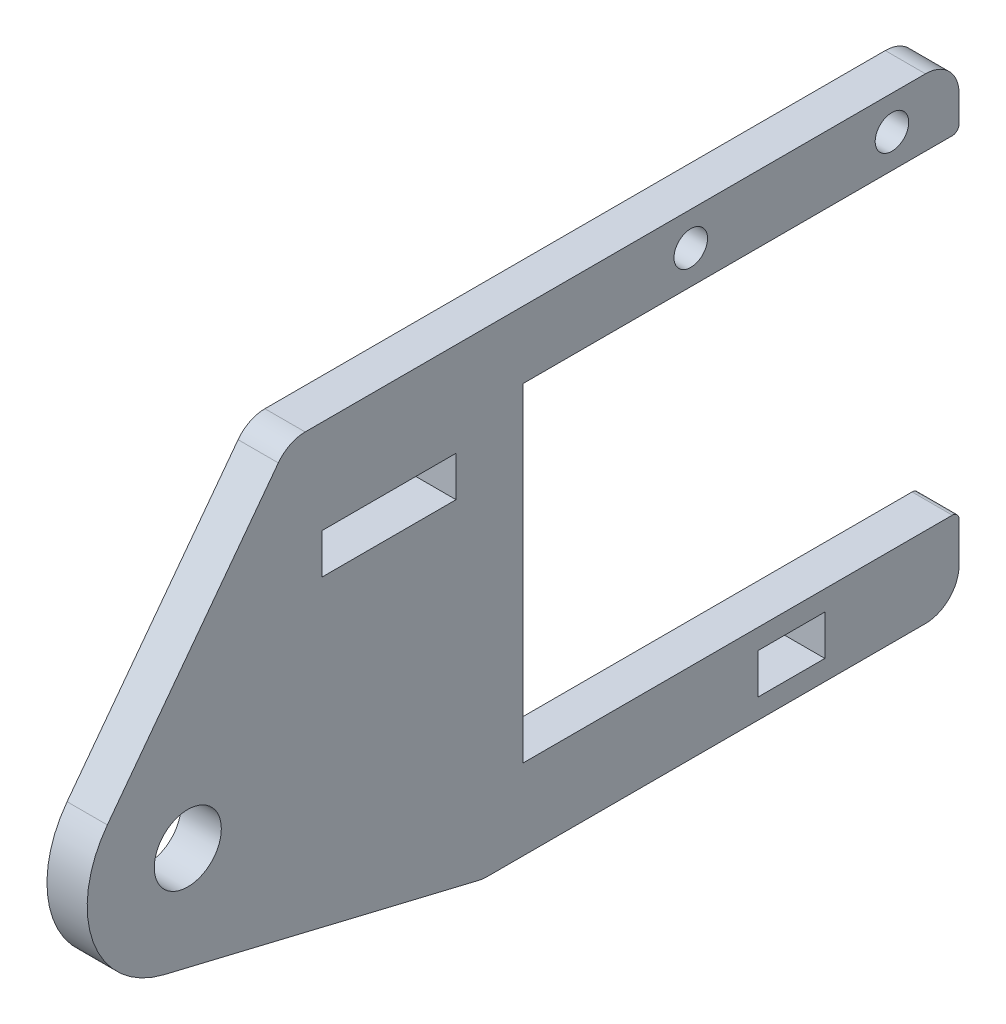
SolidWorks part; units mm, degrees
ref_plane "Front Plane" through (0, 0, 0) normal (0, 0, 1) x (1, 0, 0)
ref_plane "Top Plane" through (0, 0, 0) normal (0, 1, 0) x (1, 0, 0)
ref_plane "Right Plane" through (0, 0, 0) normal (1, 0, 0) x (0, 0, -1)
sketch "Sketch1" plane through (0, 0, 0) normal (1, 0, 0) x (0, 0, -1)
  line L0 (0, 5) -> (65, 5)
  line L1 (0, 0) -> (150, 0) construction
  line L2 (0, 0) -> (0, -34) construction
  line L3 (0, -34) -> (150, -34) construction
  line L4 (150, 0) -> (150, -34) construction
  line L5 (65, 5) -> (65, 15)
  line L6 (65, 15) -> (-35, 15)
  line L7 (-35, 15) -> (-62, -21)
  line L8 (-6, -56) -> (65, -56)
  line L9 (65, -56) -> (65, -44)
  line L10 (65, -44) -> (0, -44)
  line L11 (0, -44) -> (0, 5)
  line L12 (-30, 5) -> (-10, 5) construction
  line L13 (-10, 5) -> (-10, 11) construction
  line L14 (-10, 11) -> (-30, 11) construction
  line L15 (-30, 11) -> (-30, 5) construction
  line L16 (-50, -30) -> (-50, 5) construction
  line L17 (-50, -30) -> (-10, -30) construction
  line L18 (-65, 2.5) -> (-35, 2.5) construction
  line L19 (-65, 2.5) -> (-65, 202.5) construction
  line L20 (-65, 202.5) -> (-35, 202.5) construction
  line L21 (-35, 2.5) -> (-35, 202.5) construction
  line L22 (-10, -30) -> (-10, 5) construction
  line L23 (-30, 5) -> (-30, -30) construction
  line L24 (-6, -56) -> (-53.5047, -44.5848)
  line L25 (55, 10) -> (65, 10) construction
  line L26 (45, -47) -> (35, -47)
  line L27 (45, -47) -> (45, -53)
  line L28 (45, -53) -> (35, -53)
  line L29 (35, -47) -> (35, -53)
  line L30 (-30, 1) -> (-30, -5)
  line L31 (-30, -5) -> (-10, -5)
  line L32 (-10, -5) -> (-10, 1)
  line L33 (-10, 1) -> (-30, 1)
  circle A0 centre (-50, -30) radius 5
  arc A1 (-62, -21) -> (-53.5047, -44.5848) centre (-50, -30) ccw
  circle A2 centre (55, 10) radius 2.5
  circle A3 centre (25, 10) radius 2.5
  circle A4 centre (-50, -30) radius 15 construction
  point P10 (65, -50)
  point P21 (-20, 5)
  point P22 (-50, 2.5)
  point P24 (32.5, 5)
  point P26 (45, -50)
  point P42 (65, 10)
  dimension "D3" = 10
  dimension "D19" = 30
  dimension "D25" = 5
  dimension "D26" = 30
  dimension "D1" = 34
  dimension "D2" = 150
  dimension "D4" = 50
  dimension "D5" = 30
  dimension "D6" = 30
  dimension "D7" = 20
  dimension "D8" = 6
  dimension "D9" = 35
  dimension "D10" = 200
  dimension "D11" = 30
  dimension "D12" = 32.5
  dimension "D13" = 10
  dimension "D14" = 10
  dimension "D15" = 5
  dimension "D16" = 65
  dimension "D17" = 12
  dimension "D18" = 10
  dimension "D20" = 6
  dimension "D21" = 6
  dimension "D22" = 20
  dimension "D23" = 10
  dimension "D24" = 30
extrude "Boss-Extrude1" add sketch "Sketch1" along normal blind 6
fillet "Fillet1" radius 5 4 edges at (3, -56, 6) (3, -56, -65) (3, 15, -65) (3, 15, 35)
fillet "Fillet2" radius 1 2 edges at (3, -44, -65) (3, 5, -65)
